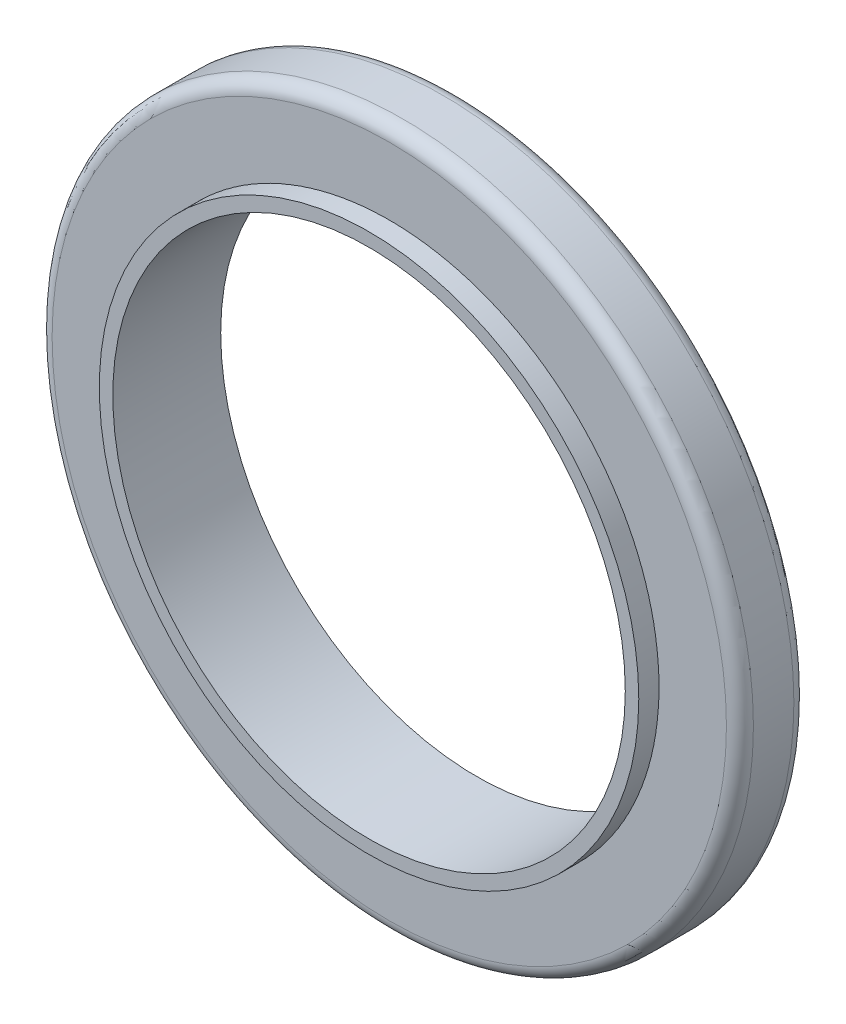
SolidWorks part; units mm, degrees
ref_plane "Front Plane" through (0, 0, 0) normal (0, 0, 1) x (1, 0, 0)
ref_plane "Top Plane" through (0, 0, 0) normal (0, 1, 0) x (1, 0, 0)
ref_plane "Right Plane" through (0, 0, 0) normal (1, 0, 0) x (0, 0, -1)
sketch "Sketch1" plane through (0, 0, 0) normal (0, 0, 1) x (1, 0, 0)
  circle A0 centre (0, -65) radius 20
  circle A1 centre (0, -65) radius 19
  arc A2 (11.8898, -90.0773) -> (-11.8898, -39.9227) centre (0, -65) ccw
  arc A3 (-11.8898, -39.9227) -> (11.8898, -90.0773) centre (0, -65) ccw
  arc A4 (11.8898, -90.0773) -> (-11.8898, -39.9227) centre (0, -65) ccw
  arc A5 (-11.8898, -39.9227) -> (11.8898, -90.0773) centre (0, -65) ccw
  dimension "D2" = 40
  dimension "D1" = 0
  dimension "D3" = 1
extrude "Boss-Extrude1" add sketch "Sketch1" against normal up to surface (8.001 mm away) contours A0 A1
ref_plane "Plane1" through (0, 0, -4.0005) normal (0, 0, -1) x (-1, 0, 0)
sketch "Sketch2" plane through (0, 0, -4.0005) normal (0, 0, -1) x (-1, 0, 0)
  circle A0 centre (0, -65) radius 20 construction
  circle A1 centre (0, -65) radius 20
  circle A2 centre (0, -65) radius 26
  dimension "D1" = 6
extrude "Boss-Extrude2" add sketch "Sketch2" along normal blind 2.5 and the other way blind 2.5 separate body
fillet "Fillet1" radius 1 2 edges at (-26, -65, -1.5005) (-26, -65, -6.5005)
sketch "Sketch3" plane through (0, 0, 0) normal (0, 0, 1) x (1, 0, 0)
  circle A0 centre (0, -65) radius 26 construction
  circle A1 centre (0, -65) radius 26
  dimension "D1" = 52
